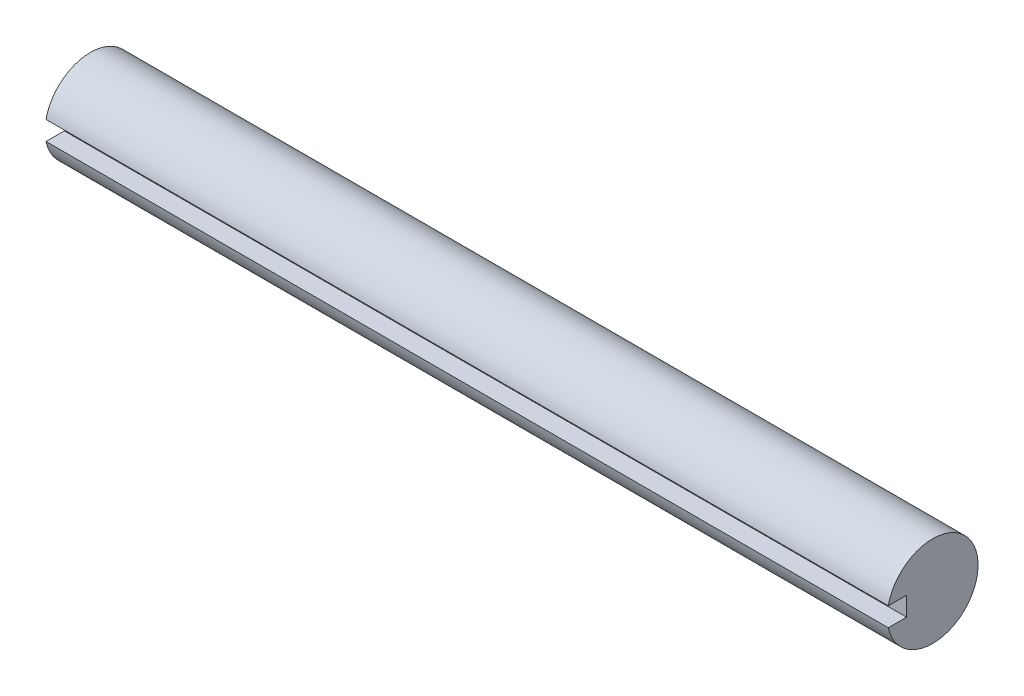
SolidWorks part; units mm, degrees
ref_plane "Front Plane" through (0, 0, 0) normal (1, 0, 0) x (0, 1, 0)
ref_plane "Top Plane" through (0, 0, 0) normal (0, 0, 1) x (0, 1, 0)
ref_plane "Right Plane" through (0, 0, 0) normal (0, 1, 0) x (-1, 0, 0)
sketch "Sketch1" plane through (0, 0, 0) normal (1, 0, 0) x (0, 1, 0)
  line L0 (-2.6, 7.1244) -> (2.6, 7.1244)
  line L1 (-2.6, 7.1244) -> (-2.6, 12.1244)
  line L2 (2.6, 7.1244) -> (2.6, 12.1244)
  circle A0 centre (0, 0) radius 12.4
  arc A1 (-2.6, 12.1244) -> (2.6, 12.1244) centre (0, 0) cw
  point P6 (0, 0)
  dimension "D1" = 24.8
  dimension "D2" = 5.2
  dimension "D3" = 5
  dimension "D4" = 5
extrude "Boss-Extrude2" add sketch "Sketch1" along normal blind 230 contours A0 | A1 L2 L0 L1
